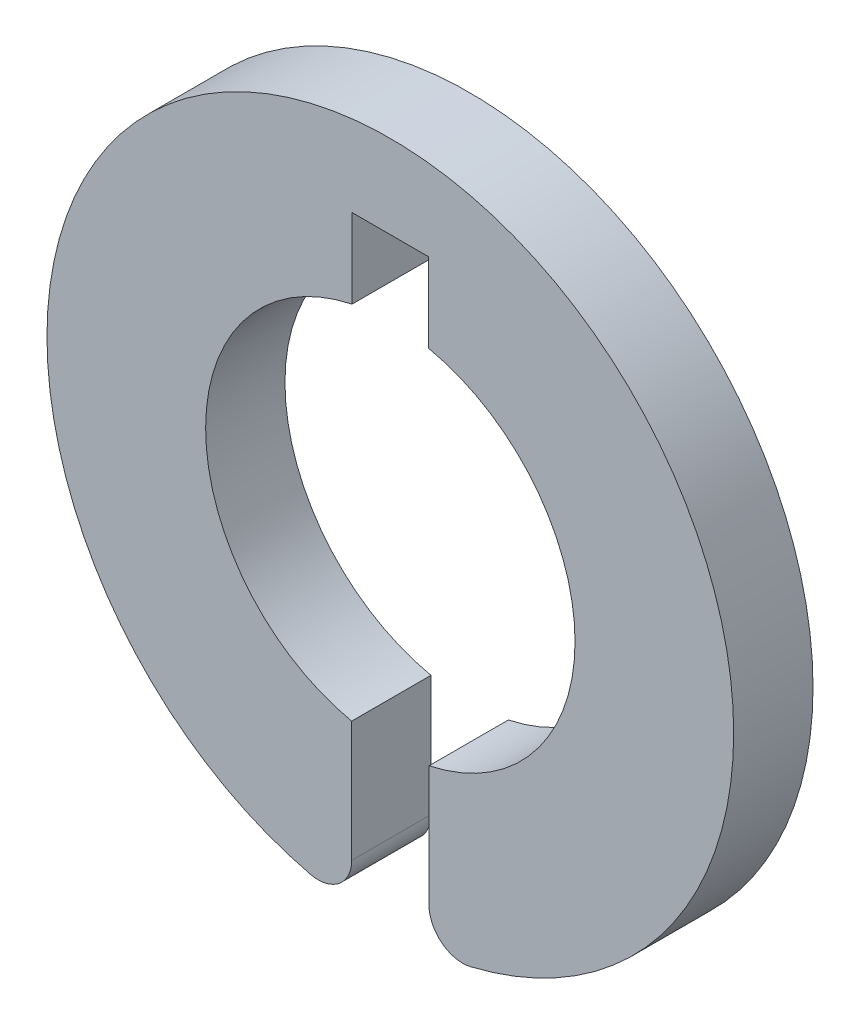
SolidWorks part; units mm, degrees
material "Acrylic (Medium-high impact)"
ref_plane "Front Plane" through (0, 0, 0) normal (0, 0, 1) x (1, 0, 0)
ref_plane "Top Plane" through (0, 0, 0) normal (0, 1, 0) x (1, 0, 0)
ref_plane "Right Plane" through (0, 0, 0) normal (1, 0, 0) x (0, 0, -1)
sketch "스케치1" plane through (0, 0, 0) normal (0, 0, 1) x (1, 0, 0)
  line L0 (0, 10.85) -> (0, 0) construction
  line L6 (-1.4475, 9.8334) -> (1.4475, 9.8334)
  line L7 (0, 0) -> (0, -9.8663) construction
  line L8 (-1.4625, -12.9024) -> (1.4625, -12.9024) construction
  line L9 (-1.4625, -12.9024) -> (-1.4625, -6.8302)
  line L10 (-1.4625, -6.8302) -> (1.4625, -6.8302) construction
  line L11 (1.4625, -12.9024) -> (1.4625, -6.8302)
  line L12 (-1.4625, -12.9024) -> (1.4625, -6.8302) construction
  line L13 (-1.4625, -6.8302) -> (1.4625, -12.9024) construction
  line L14 (-1.4475, 9.8334) -> (-1.4475, 6.8334)
  line L15 (-1.4475, 6.8334) -> (1.4475, 6.8334) construction
  line L16 (1.4475, 9.8334) -> (1.4475, 6.8334)
  line L17 (-1.4475, 9.8334) -> (1.4475, 6.8334) construction
  line L18 (-1.4475, 6.8334) -> (1.4475, 9.8334) construction
  circle A0 centre (0, 0) radius 12.985 construction
  circle A1 centre (0, 0) radius 6.985 construction
  arc A2 (-1.4625, -12.9024) -> (1.4625, -12.9024) centre (0, 0) cw
  arc A3 (1.4625, -6.8302) -> (1.4475, 6.8334) centre (0, 0) ccw
  arc A4 (-1.4475, 6.8334) -> (-1.4625, -6.8302) centre (0, 0) ccw
  point P2 (0, 10.85)
  point P5 (0, 8.3334)
  point P10 (0, -9.8663)
  dimension "D1" = 6
  dimension "D2" = 13.97
  dimension "D3" = 2.895
  dimension "D4" = 3
  dimension "D5" = 2.925
extrude "보스-돌출1" add sketch "스케치1" along normal blind 3
fillet "필렛1" radius 1.27 2 edges at (-1.4625, -12.9024, 1.5) (1.4625, -12.9024, 1.5)
